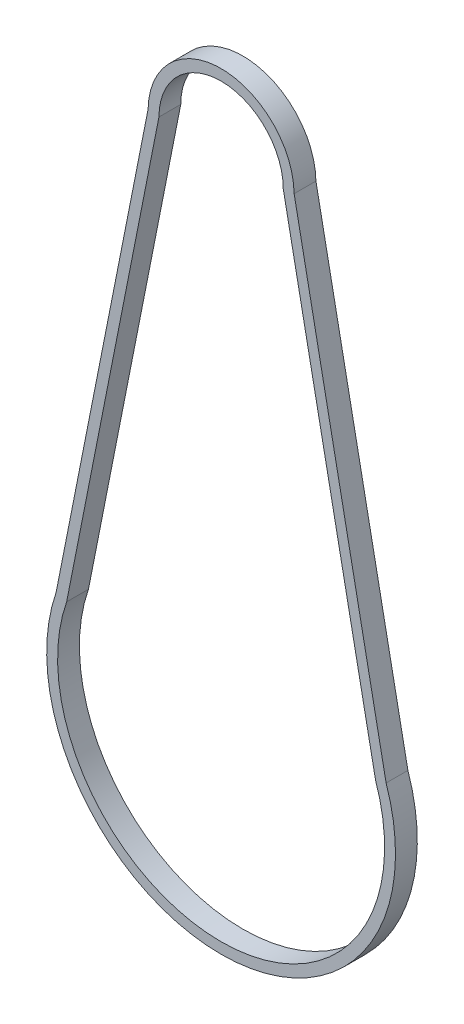
SolidWorks part; units mm, degrees
ref_plane "Front Plane" through (0, 0, 0) normal (0, 0, 1) x (1, 0, 0)
ref_plane "Top Plane" through (0, 0, 0) normal (0, 1, 0) x (1, 0, 0)
ref_plane "Right Plane" through (0, 0, 0) normal (1, 0, 0) x (0, 0, -1)
sketch "Sketch1" plane through (0, 0, 0) normal (0, 0, 1) x (1, 0, 0)
  line L0 (-2.85, 31.34) -> (-7.085, 9.9602)
  line L1 (-3.3496, 31.391) -> (-7.5688, 10.0909)
  line L2 (2.85, 31.34) -> (7.085, 9.9602)
  line L3 (3.3496, 31.391) -> (7.5688, 10.0909)
  arc A0 (2.85, 31.34) -> (-2.85, 31.34) centre (0, 31.34) ccw
  arc A1 (-7.085, 9.9602) -> (7.085, 9.9602) centre (0, 7.5) ccw
  arc A2 (3.3496, 31.391) -> (-3.3496, 31.391) centre (0, 31.34) ccw
  arc A3 (-7.5688, 10.0909) -> (7.5688, 10.0909) centre (0, 7.5) ccw
  dimension "D1" = 0.5
extrude "Boss-Extrude2" add sketch "Sketch1" along normal mid plane 1
